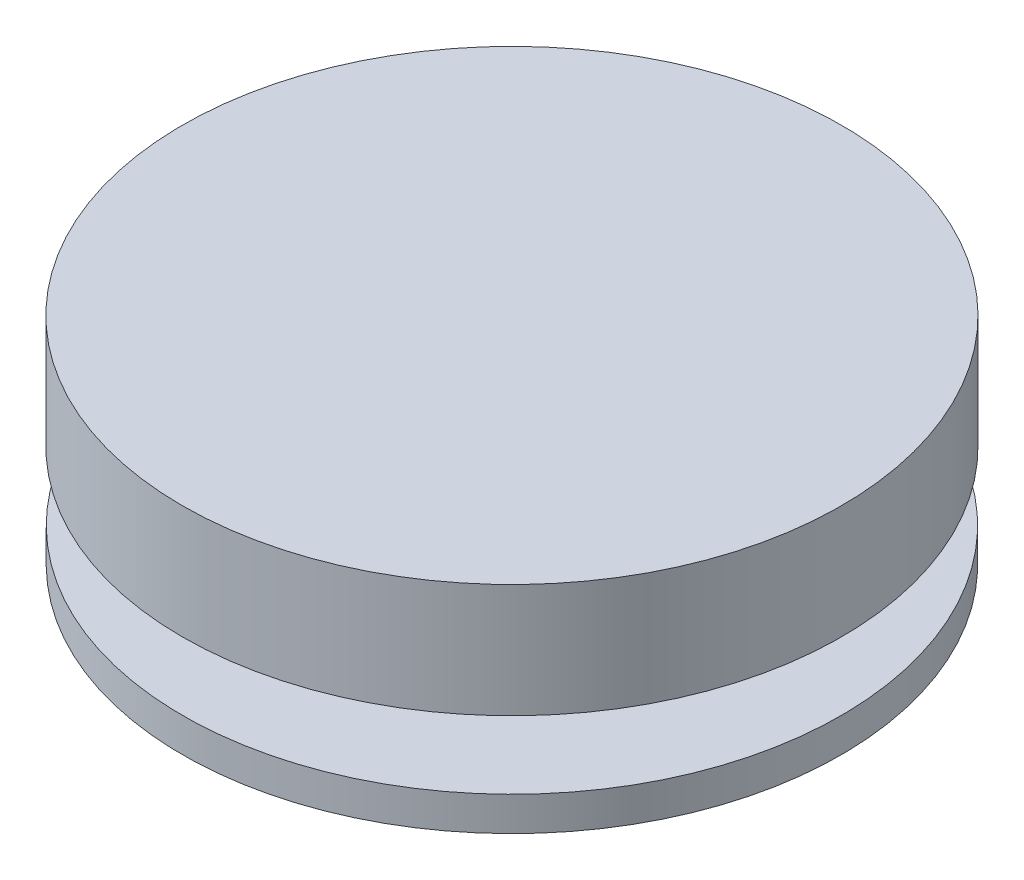
SolidWorks part; units mm, degrees
ref_plane "Front Plane" through (0, 0, 0) normal (0, 0, 1) x (1, 0, 0)
ref_plane "Top Plane" through (0, 0, 0) normal (0, 1, 0) x (1, 0, 0)
ref_plane "Right Plane" through (0, 0, 0) normal (1, 0, 0) x (0, 0, -1)
sketch "Sketch1" plane through (0, 0, 0) normal (0, 1, 0) x (1, 0, 0)
  circle A0 centre (0, 0) radius 36.8
extrude "Boss-Extrude1" add sketch "Sketch1" along normal blind 3.81
sketch "Sketch2" plane through (0, 3.81, 0) normal (0, 1, 0) x (1, 0, 0)
  circle A0 centre (0, 0) radius 15.24
extrude "Boss-Extrude2" add sketch "Sketch2" along normal blind 7.62
sketch "Sketch3" plane through (0, 11.43, 0) normal (0, 1, 0) x (1, 0, 0)
  circle A0 centre (0, 0) radius 36.83
extrude "Boss-Extrude3" add sketch "Sketch3" along normal blind 12.7
